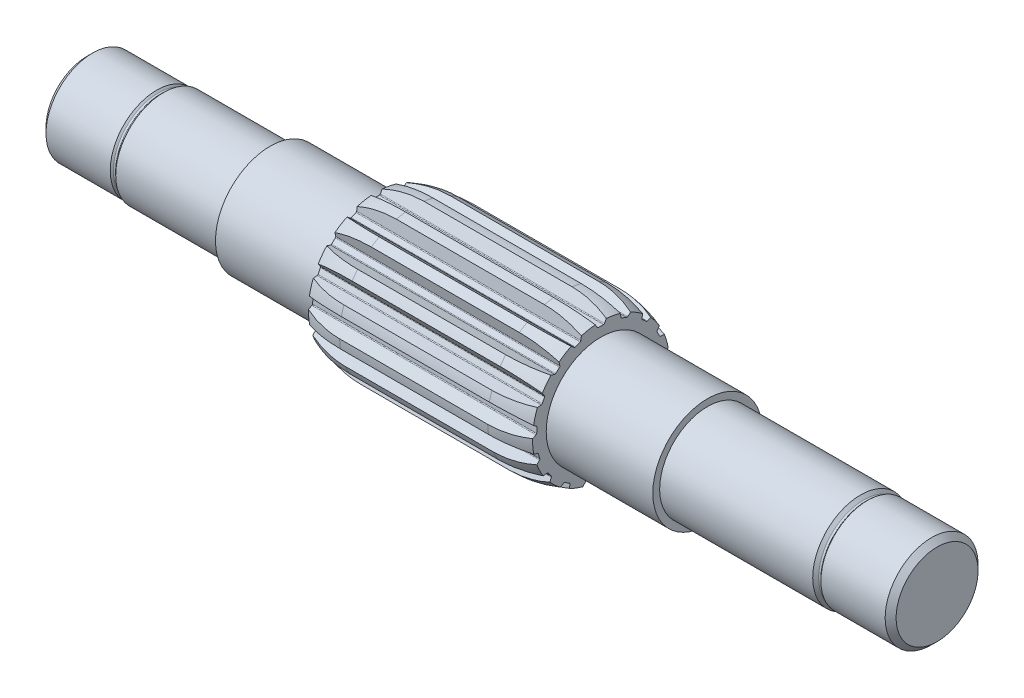
SolidWorks part; units mm, degrees
ref_plane "Plan1" through (0, 0, 0) normal (0, 0, 1) x (1, 0, 0)
ref_plane "Plan2" through (0, 0, 0) normal (0, 1, 0) x (1, 0, 0)
ref_plane "Plan3" through (0, 0, 0) normal (1, 0, 0) x (0, 0, -1)
sketch "Esquisse1" plane through (0, 0, 0) normal (0, 0, 1) x (1, 0, 0)
  line L0 (-10, 0) -> (162.4199, 0) construction
  line L1 (0, 0) -> (0, 7.5)
  line L2 (0, 7.5) -> (1, 8.5)
  line L3 (1, 8.5) -> (12.75, 8.5)
  line L4 (53, 12.5) -> (53, 10)
  line L5 (53, 10) -> (33.5, 10)
  line L6 (33.5, 10) -> (33.5, 8.75)
  line L7 (33.5, 8.75) -> (14, 8.75)
  line L8 (14, 8.75) -> (13.4621, 8.2121)
  line L9 (59.9597, 13.75) -> (87.0403, 13.75)
  line L10 (13.0379, 8.2121) -> (12.75, 8.5)
  line L11 (94, 12.5) -> (94, 10)
  line L12 (94, 10) -> (113.5, 10)
  line L13 (113.5, 10) -> (113.5, 8.75)
  line L14 (113.5, 8.75) -> (141.5, 8.75)
  line L15 (141.5, 8.75) -> (142.0379, 8.2121)
  line L16 (142.4621, 8.2121) -> (142.75, 8.5)
  line L17 (142.75, 8.5) -> (154.5, 8.5)
  line L18 (154.5, 8.5) -> (155.5, 7.5)
  line L19 (155.5, 7.5) -> (155.5, 0)
  line L20 (155.5, 0) -> (0, 0)
  arc A0 (94, 12.5) -> (87.0403, 13.75) centre (87.0403, -6.25) ccw
  arc A1 (53, 12.5) -> (59.9597, 13.75) centre (59.9597, -6.25) cw
  arc A2 (13.4621, 8.2121) -> (13.0379, 8.2121) centre (13.25, 8.4243) cw
  arc A3 (142.4621, 8.2121) -> (142.0379, 8.2121) centre (142.25, 8.4243) cw
  point P25 (13.25, 8)
  point P28 (142.25, 8)
  dimension "D36" = 20
  dimension "D37" = 20
  dimension "D15" = 0.3
  dimension "D1" = 8.5
  dimension "D2" = 41
  dimension "D3" = 19.5
  dimension "D4" = 19.5
  dimension "D5" = 28
  dimension "D6" = 14
  dimension "D7" = 14
  dimension "D8" = 45
  dimension "D9" = 45
  dimension "D10" = 2.5
  dimension "D11" = 8.75
  dimension "D12" = 10
  dimension "D13" = 13.75
  dimension "D14" = 0.5
  dimension "D16" = 155.5
  dimension "D29" = 45
  dimension "D30" = 1
revolve "Base-Révolution" add sketch "Esquisse1" angle 360 about L0
sketch "Esquisse3" plane through (0, 0, 0) normal (0, 0, 1) x (1, 0, 0)
  line L2 (53, 12.5) -> (53, -12.5) construction
  line L3 (-10, 0) -> (162.4199, 0) construction
  point P0 (53, 0)
ref_plane "Plan4" through (53, 0, 0) normal (1, 0, 0) x (0, 0, -1)
sketch "fin rainure" plane through (0, 0, 0) normal (0, 0, 1) x (1, 0, 0)
  line L1 (94, -12.5) -> (94, 12.5) construction
  line L2 (-10, 0) -> (162.4199, 0) construction
  point P0 (94, 0)
ref_plane "Plan fin rainure" through (94, 0, 0) normal (1, 0, 0) x (0, 0, -1)
sketch "Esquisse4" plane through (53, 0, 0) normal (1, 0, 0) x (0, 0, -1)
  line L0 (1.75, 13.75) -> (-1.75, 13.75)
  line L1 (-0.653, 11.85) -> (-1.75, 13.75)
  line L2 (-0.4798, 11.75) -> (0.4798, 11.75)
  line L3 (0.653, 11.85) -> (1.75, 13.75)
  line L4 (0, 51.2304) -> (0, 44.2344) construction
  line L5 (0, 50) -> (0, -50) construction
  arc A0 (0.4798, 11.75) -> (0.653, 11.85) centre (0.4798, 11.95) ccw
  arc A1 (-0.4798, 11.75) -> (-0.653, 11.85) centre (-0.4798, 11.95) cw
  circle A3 centre (0, 0) radius 13.75 construction
  point P6 (0, 13.75)
  point P12 (0, 11.75)
  dimension "D2" = 0.2
  dimension "D1" = 30
  dimension "D3" = 2
  dimension "D4" = 3.5
extrude "Enlèv. mat.-Extru.1" cut sketch "Esquisse4" along normal up to surface (41 mm away)
pattern_circular "Répétition circulaire1" count 17 over 360 about axis through (-10, 0, 0) along (1, 0, 0)
hole_wizard "Perçage1" positions "Esquisse6" profile "Esquisse5" legacy
sketch "Esquisse6" plane through (0, 0, 0) normal (-1, 0, 0) x (0, 0, 1)
  point P0 (0, 0)
sketch "Esquisse5" plane through (0, 0, 0) normal (0, 1, 0) x (0, 0, 1)
  line L0 (0, 0) -> (0, 6.6009)
  line L1 (0, 6.6009) -> (1, 6)
  line L2 (1, 6) -> (1, 2.1826)
  line L3 (1, 2.1826) -> (3, 0)
  line L4 (3, 0) -> (0, 0)
  line L5 (0, -14.3089) -> (0, 102.4216) construction
  line L6 (0, 6.6009) -> (-1, 6) construction
  line L7 (-1, 2.1826) -> (-3, 0) construction
  dimension "Diamètre" = 2
  dimension "Profondeur" = 6
  dimension "Diamètre fraisé" = 6
  dimension "Angle fraisé" = 85
  dimension "Angle" = 118
